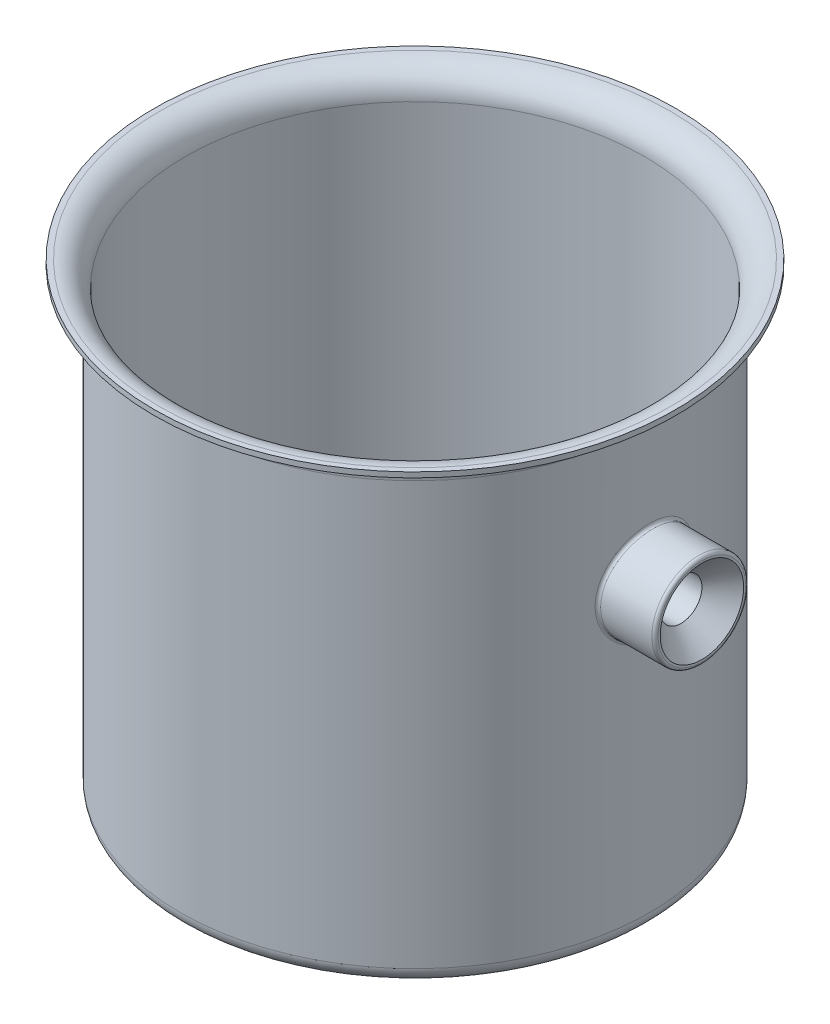
SolidWorks part; units mm, degrees
ref_plane "Front Plane" through (0, 0, 0) normal (0, 0, 1) x (1, 0, 0)
ref_plane "Top Plane" through (0, 0, 0) normal (0, 1, 0) x (1, 0, 0)
ref_plane "Right Plane" through (0, 0, 0) normal (1, 0, 0) x (0, 0, -1)
sketch "Sketch1" plane through (0, 0, 0) normal (0, 0, 1) x (1, 0, 0)
  line L0 (0, 205) -> (0, 247.4541) construction
  line L1 (-21, 199.1452) -> (-4, 199.1452)
  line L2 (-22.5, 200.6452) -> (-22.5, 241.1452)
  line L3 (-25, 243.1452) -> (-24.5, 243.1452)
  line L4 (22.5, 200.6452) -> (22.5, 241.1452)
  line L5 (4, 205) -> (-4, 205) construction
  line L6 (15, 199.1452) -> (-15, 199.1452) construction
  line L7 (24.5, 243.1452) -> (25, 243.1452)
  line L8 (-25, 243.6452) -> (-24.5, 243.6452)
  line L9 (-22, 200.6452) -> (-22, 241.1452)
  line L10 (-21, 199.6452) -> (-4, 199.6452)
  line L11 (22, 200.6452) -> (22, 241.1452)
  line L12 (24.5, 243.6452) -> (25, 243.6452)
  line L13 (25, 243.1452) -> (25, 243.6452)
  line L14 (-25, 243.6452) -> (-25, 243.1452)
  line L15 (-4, 199.6452) -> (-4, 199.1452)
  line L16 (-4, 205) -> (-4, 29.2) construction
  line L17 (4, 199.6452) -> (4, 199.1452)
  line L18 (4, 5) -> (4, 205) construction
  line L19 (4, 199.6452) -> (21, 199.6452)
  line L20 (4, 199.1452) -> (21, 199.1452)
  line L21 (-21, 199.6452) -> (21, 199.6452) construction
  line L23 (-21, 199.1452) -> (21, 199.1452) construction
  arc A0 (24.5, 243.1452) -> (22.5, 241.1452) centre (24.5, 241.1452) ccw
  arc A1 (-22.5, 241.1452) -> (-24.5, 243.1452) centre (-24.5, 241.1452) ccw
  arc A2 (21, 199.1452) -> (22.5, 200.6452) centre (21, 200.6452) ccw
  arc A3 (-21, 199.1452) -> (-22.5, 200.6452) centre (-21, 200.6452) cw
  arc A4 (-22, 241.1452) -> (-24.5, 243.6452) centre (-24.5, 241.1452) ccw
  arc A5 (-21, 199.6452) -> (-22, 200.6452) centre (-21, 200.6452) cw
  arc A6 (21, 199.6452) -> (22, 200.6452) centre (21, 200.6452) ccw
  arc A7 (24.5, 243.6452) -> (22, 241.1452) centre (24.5, 241.1452) ccw
  point P15 (22.5, 243.1452)
  point P18 (-22.5, 243.1452)
  point P23 (-22.5, 199.1452)
  dimension "D4" = 2
  dimension "D5" = 1.5
  dimension "D1" = 44
  dimension "D2" = 45
  dimension "D3" = 50
  dimension "D6" = 0.5
revolve "Revolve2" add sketch "Sketch1" angle 360 about L0
ref_plane "Plane1" through (27.5, 0, 0) normal (1, 0, 0) x (0, 0, -1)
sketch "Sketch4" plane through (27.5, 0, 0) normal (1, 0, 0) x (0, 0, -1)
  line L0 (25, 243.6452) -> (-25, 243.6452) construction
  circle A0 centre (0, 228.1452) radius 4.5
  circle A1 centre (0, 228.1452) radius 2
  dimension "D2" = 9
  dimension "D3" = 4
  dimension "D1" = 15.5
extrude "Boss-Extrude1" add sketch "Sketch4" against normal up to surface (5.4546 mm away)
sketch "Sketch5" plane through (27.5, 0, 0) normal (1, 0, 0) x (0, 0, -1)
  circle A0 centre (0, 228.1452) radius 2
extrude "Cut-Extrude1" cut sketch "Sketch5" against normal blind 10
chamfer "Chamfer1" distance 2 angle 45 1 edges at (27.5, 228.1452, -2)
fillet "Fillet1" radius 0.3 2 edges at (27.5, 228.1452, -4.5) (22.0652, 227.2098, 4.4017)
